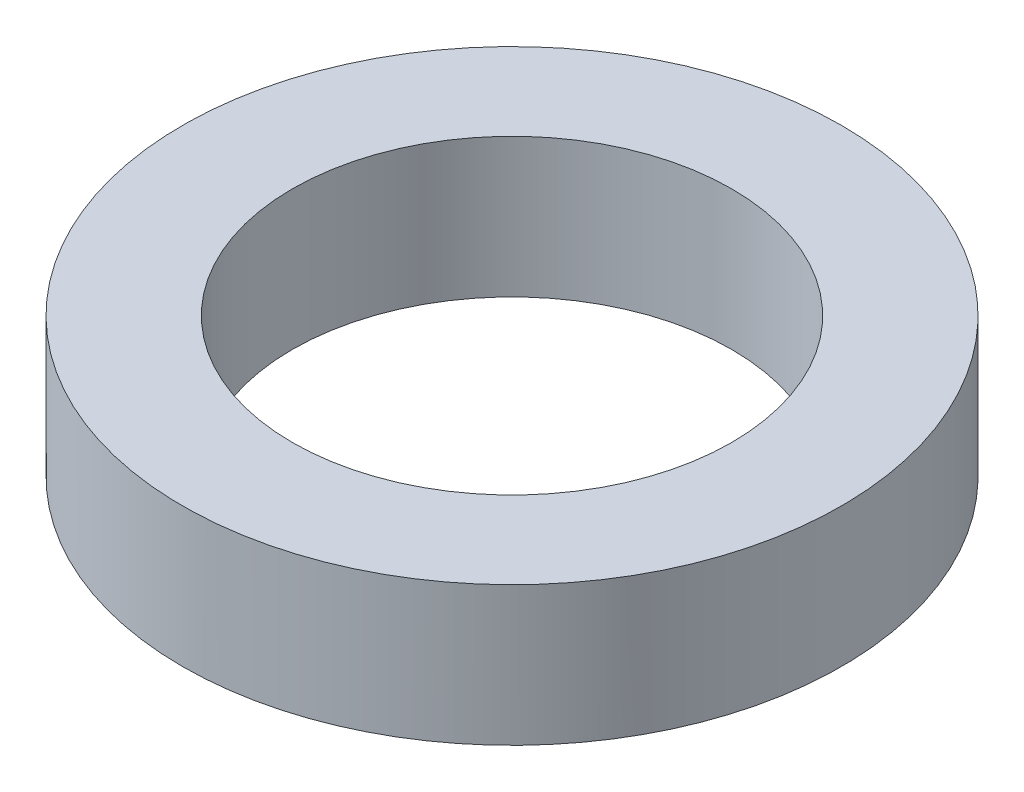
SolidWorks part; units mm, degrees
material "Epoxy, Unfilled"
ref_plane "Front Plane" through (0, 0, 0) normal (0, 0, 1) x (1, 0, 0)
ref_plane "Top Plane" through (0, 0, 0) normal (0, 1, 0) x (1, 0, 0)
ref_plane "Right Plane" through (0, 0, 0) normal (1, 0, 0) x (0, 0, -1)
sketch "Sketch1" plane through (0, 0, 0) normal (0, 1, 0) x (1, 0, 0)
  circle A0 centre (0, 0) radius 7.62
  circle A1 centre (0, 0) radius 11.43
  dimension "D1" = 15.24
  dimension "D2" = 3.81
extrude "Boss-Extrude1" add sketch "Sketch1" along normal up to surface (4.826 mm away)
